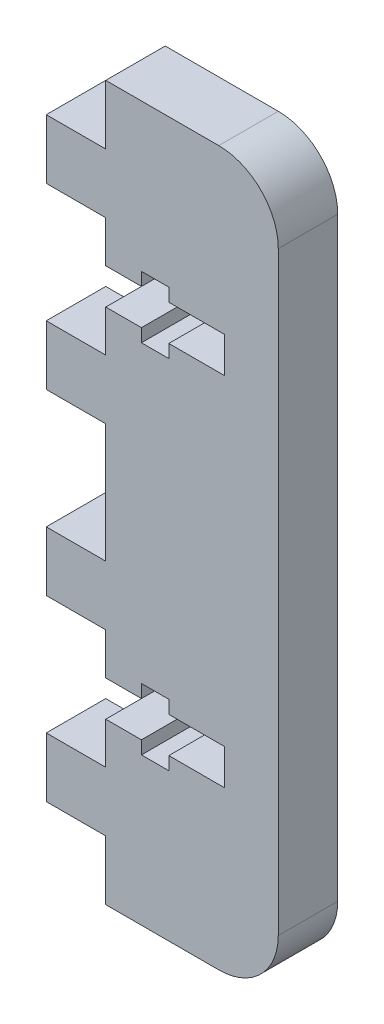
SolidWorks part; units mm, degrees
ref_plane "Front Plane" through (0, 0, 0) normal (0, 0, 1) x (1, 0, 0)
ref_plane "Top Plane" through (0, 0, 0) normal (0, 1, 0) x (1, 0, 0)
ref_plane "Right Plane" through (0, 0, 0) normal (1, 0, 0) x (0, 0, -1)
sketch "Sketch1" plane through (0, 0, 0) normal (0, 0, 1) x (1, 0, 0)
  line L0 (0, 60) -> (0, 55)
  line L1 (0, 0) -> (14.5, 0)
  line L2 (0, 0) -> (0, 60) construction
  line L3 (0, 60) -> (14.5, 60)
  line L4 (14.5, 0) -> (14.5, 60)
  line L5 (0, 35) -> (0, 25)
  line L6 (0, 5) -> (0, 0)
  line L7 (0, 45) -> (11.2208, 45) construction
  line L8 (0, 46.5) -> (0, 50)
  line L9 (-5, 50) -> (-5, 55)
  line L10 (-5, 55) -> (0, 55)
  line L11 (-5, 50) -> (0, 50)
  line L12 (0, 43.5) -> (0, 40)
  line L13 (0, 40) -> (-5, 40)
  line L14 (-5, 40) -> (-5, 35)
  line L15 (-5, 35) -> (0, 35)
  line L16 (0, 15) -> (11.2208, 15) construction
  line L17 (0, 16.5) -> (0, 20)
  line L18 (-5, 20) -> (-5, 25)
  line L19 (-5, 25) -> (0, 25)
  line L20 (-5, 20) -> (0, 20)
  line L21 (0, 13.5) -> (0, 10)
  line L22 (0, 10) -> (-5, 10)
  line L23 (-5, 10) -> (-5, 5)
  line L24 (-5, 5) -> (0, 5)
  line L25 (0, 46.5) -> (0, 43.5) construction
  line L26 (0, 43.5) -> (3, 43.5)
  line L27 (5.3, 43.5) -> (5.3, 42.4)
  line L28 (3, 47.6) -> (5.3, 47.6)
  line L29 (3, 42.4) -> (3, 43.5)
  line L30 (5.3, 43.5) -> (10, 43.5)
  line L31 (10, 43.5) -> (10, 46.5)
  line L32 (10, 46.5) -> (5.3, 46.5)
  line L33 (3, 46.5) -> (3, 47.6)
  line L34 (5.3, 42.4) -> (3, 42.4)
  line L35 (5.3, 47.6) -> (5.3, 46.5)
  line L36 (3, 46.5) -> (0, 46.5)
  line L37 (10, 45) -> (0, 45) construction
  line L38 (0, 16.5) -> (0, 13.5) construction
  line L39 (0, 13.5) -> (3, 13.5)
  line L40 (5.3, 13.5) -> (5.3, 12.4)
  line L41 (3, 17.6) -> (5.3, 17.6)
  line L42 (3, 12.4) -> (3, 13.5)
  line L43 (5.3, 13.5) -> (10, 13.5)
  line L44 (10, 13.5) -> (10, 16.5)
  line L45 (10, 16.5) -> (5.3, 16.5)
  line L46 (3, 16.5) -> (3, 17.6)
  line L47 (5.3, 12.4) -> (3, 12.4)
  line L48 (5.3, 17.6) -> (5.3, 16.5)
  line L49 (3, 16.5) -> (0, 16.5)
  line L50 (10, 15) -> (0, 15) construction
  point P11 (-2.5, 25)
  point P12 (-2.5, 5)
  dimension "D1" = 10
  dimension "D2" = 5
  dimension "D3" = 5
  dimension "D4" = 10
  dimension "16.8" = 14.5
  dimension "D5" = 5
  dimension "D6" = 5
  dimension "D7" = 10
  dimension "D8" = 5
  dimension "D9" = 5
  dimension "D10" = 5.2
  dimension "D11" = 3
  dimension "D12" = 2.3
  dimension "D13" = 3
  dimension "D14" = 10
  dimension "D15" = 5.2
  dimension "D16" = 3
  dimension "D17" = 2.3
  dimension "D18" = 3
  dimension "D19" = 10
extrude "Boss-Extrude1" add sketch "Sketch1" along normal blind 5
fillet "Fillet1" radius 5 2 edges at (14.5, 0, 2.5) (14.5, 60, 2.5)
